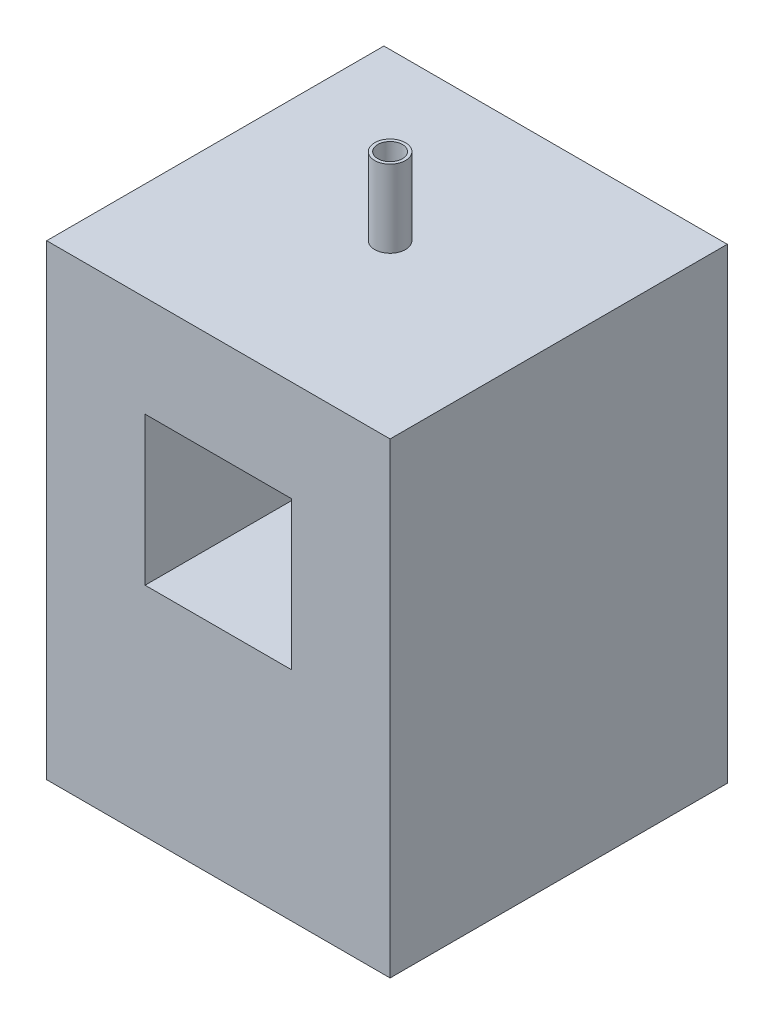
SolidWorks part; units mm, degrees
ref_plane "Front Plane" through (0, 0, 0) normal (0, 0, 1) x (1, 0, 0)
ref_plane "Top Plane" through (0, 0, 0) normal (0, 1, 0) x (1, 0, 0)
ref_plane "Right Plane" through (0, 0, 0) normal (1, 0, 0) x (0, 0, -1)
sketch "Sketch1" plane through (0, 0, 0) normal (0, 0, 1) x (1, 0, 0)
  line L1 (141.2875, 192.0875) -> (-141.2875, 192.0875)
  line L2 (141.2875, 192.0875) -> (141.2875, -192.0875)
  line L3 (141.2875, -192.0875) -> (-141.2875, -192.0875)
  line L4 (-141.2875, 192.0875) -> (-141.2875, -192.0875)
  line L5 (141.2875, 192.0875) -> (-141.2875, -192.0875) construction
  line L6 (141.2875, -192.0875) -> (-141.2875, 192.0875) construction
  line L12 (52.3875, -14.1896) -> (-52.3875, 106.4604) construction
  line L13 (52.3875, 106.4604) -> (-52.3875, -14.1896) construction
  point P0 (0, 0)
  point P8 (0, 46.1354)
extrude "Cell body" add sketch "Sketch1" against normal blind 277.495
sketch "Sketch5" plane through (0, 0, 0) normal (0, 0, 1) x (1, 0, 0)
  line L7 (60.325, -12.9704) -> (-60.325, -12.9704)
  line L8 (60.325, -12.9704) -> (60.325, 108.9496)
  line L9 (60.325, 108.9496) -> (-60.325, 108.9496)
  line L10 (-60.325, -12.9704) -> (-60.325, 108.9496)
  line L11 (60.325, -12.9704) -> (-60.325, 108.9496) construction
  line L12 (60.325, 108.9496) -> (-60.325, -12.9704) construction
  point P0 (0, 47.9896)
extrude "see-through hole" cut sketch "Sketch5" against normal blind 282.575
sketch "Sketch6" plane through (0, 192.0875, 0) normal (0, 1, 0) x (1, 0, 0)
  circle A0 centre (0, 141.2875) radius 12.7
extrude "Chimney" add sketch "Sketch6" along normal blind 63.5 contours A0
sketch "Sketch9" plane through (0, 255.5875, 0) normal (0, 1, 0) x (1, 0, 0)
  circle A0 centre (0, 141.2875) radius 10.16
extrude "Chimney counterbore" cut sketch "Sketch9" against normal blind 50.8
sketch "Sketch10" plane through (0, 204.7875, 0) normal (0, 1, 0) x (1, 0, 0)
  circle A0 centre (0, 141.2875) radius 5.5666
extrude "Chimney hole" cut sketch "Sketch10" against normal blind 98.806
